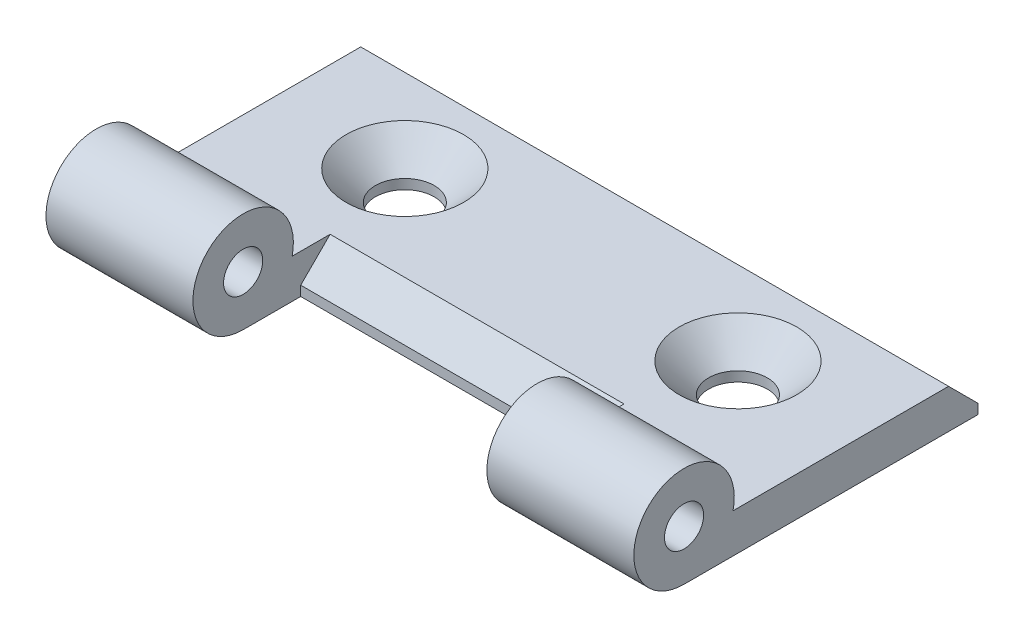
SolidWorks part; units mm, degrees
ref_plane "前视基准面" through (0, 0, 0) normal (0, 0, 1) x (1, 0, 0)
ref_plane "上视基准面" through (0, 0, 0) normal (0, 1, 0) x (1, 0, 0)
ref_plane "右视基准面" through (0, 0, 0) normal (1, 0, 0) x (0, 0, -1)
sketch "草图1" plane through (0, 0, 0) normal (1, 0, 0) x (0, 0, -1)
  line L1 (0, 0) -> (30, 0)
  line L3 (5, 4) -> (30, 4)
  line L4 (30, 0) -> (30, 4)
  circle A0 centre (0, 5.125) radius 2
  arc A1 (5, 4) -> (0, 0) centre (0, 5.125) ccw
  dimension "D4" = 4
  dimension "D1" = 25
  dimension "D2" = 30
  dimension "D3" = 4
extrude "凸台-拉伸1" add sketch "草图1" along normal mid plane 60
sketch "草图2" plane through (0, 0, 0) normal (0, 1, 0) x (1, 0, 0)
  line L0 (-30, -5.125) -> (30, -5.125) construction
  line L1 (-15, 5.875) -> (15, 5.875)
  line L2 (-15, 5.875) -> (-15, -5.125)
  line L3 (-15, -5.125) -> (15, -5.125)
  line L4 (15, 5.875) -> (15, -5.125)
  line L5 (0, 0) -> (0, 22.9721) construction
  circle A0 centre (-17, 18.5) radius 3
  circle A1 centre (17, 18.5) radius 3
  dimension "D2" = 6
  dimension "D1" = 11
  dimension "D3" = 34
  dimension "D4" = 30
  dimension "D5" = 18.5
extrude "切除-拉伸1" cut sketch "草图2" along normal through all
chamfer "倒角1" distance 3 angle 45 4 edges at (0, 4, -5.875) (-17, 4, -21.5) (17, 4, -21.5) (0, 4, -30)
